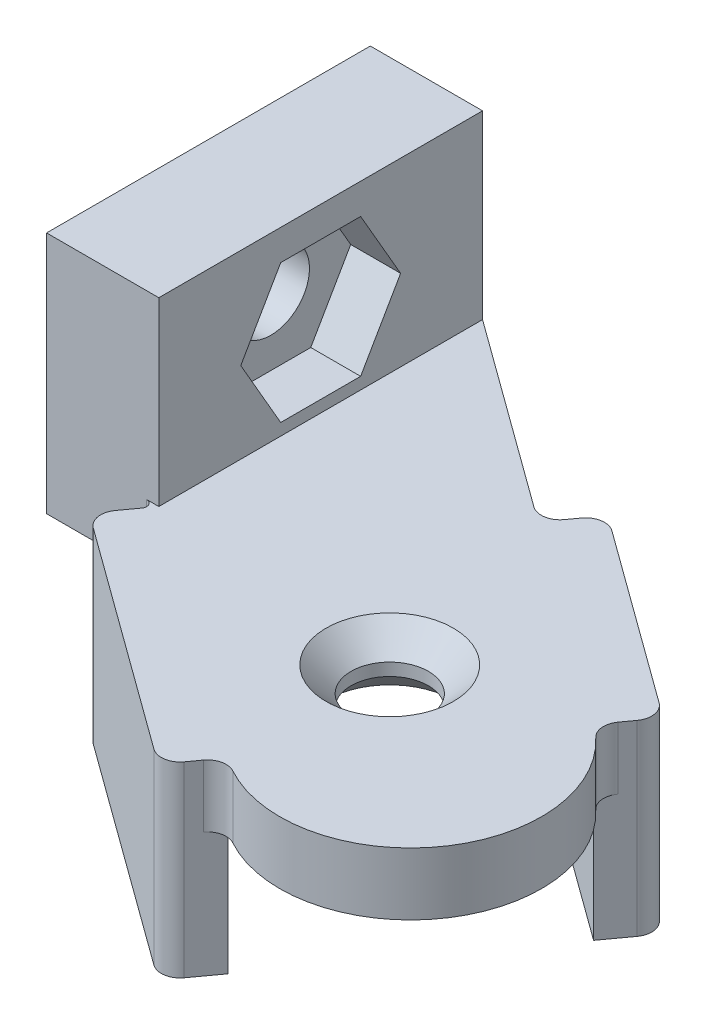
SolidWorks part; units mm, degrees
material "PA 类型 6"
ref_plane "前视基准面" through (0, 0, 0) normal (0, 0, 1) x (1, 0, 0)
ref_plane "上视基准面" through (0, 0, 0) normal (0, 1, 0) x (1, 0, 0)
ref_plane "右视基准面" through (0, 0, 0) normal (1, 0, 0) x (0, 0, -1)
sketch "草图1" plane through (0, 0, 0) normal (0, 1, 0) x (1, 0, 0)
  line L0 (0, 0) -> (0, 12.2017) construction
  line L1 (0, 0) -> (15.21, 0) construction
  line L2 (0, 0) -> (11.3188, 8.2236) construction
  line L5 (6.1542, 2.018) -> (-0.0175, -6.4766) construction
  line L7 (-10.1244, 13.8452) -> (6.1542, 2.018)
  line L8 (-10.1244, 0.8664) -> (-0.0175, -6.4766)
  line L9 (-10.1244, 13.8452) -> (-10.1244, 0.8664)
  line L10 (0, 0) -> (-11.3188, 8.2236) construction
  circle A0 centre (0, 0) radius 1.55
  arc A2 (6.1542, 2.018) -> (-0.0175, -6.4766) centre (3.0684, -2.2293) cw
  dimension "D1" = 3.1
  dimension "D5" = 5.25
  dimension "D2" = 36
  dimension "D6" = 10.1244
  dimension "D7" = 5.25
extrude "基座" add sketch "草图1" along normal blind 2.5
sketch "草图2" plane through (0, 0, 0) normal (0, 1, 0) x (1, 0, 0)
  line L3 (6.1542, 2.018) -> (-10.1244, 13.8452) construction
  line L5 (0, 0) -> (19.4408, 0) construction
  line L6 (6.1542, 2.018) -> (-10.1244, 13.8452) construction
  line L7 (0, 0) -> (0, 16.8119) construction
  line L14 (0, 0) -> (-14.65, 10.6439) construction
  line L15 (-11.3, -0.7516) -> (-10.1244, 0.8664)
  line L16 (-1.1931, -8.0947) -> (-11.3, -0.7516)
  line L17 (-0.0175, -6.4766) -> (-1.1931, -8.0947)
  line L18 (-10.1244, 0.8664) -> (-0.0175, -6.4766)
  line L19 (7.3298, 3.6361) -> (-0.8095, 9.5496)
  line L20 (6.1542, 2.018) -> (7.3298, 3.6361)
  line L21 (-1.9851, 7.9316) -> (6.1542, 2.018)
  line L22 (-0.8095, 9.5496) -> (-1.9851, 7.9316)
  point P6 (-1.9851, 7.9316)
  dimension "D1" = 36
  dimension "D2" = 2
extrude "机臂限位" add sketch "草图2" against normal blind 7.5 from surface at 2.5 contours L18 L15 L16 L17 | L19 L22 L21 L20 starting at face at (-2.4662, 2.5, -1.7918)
sketch "草图3" plane through (0, 0, 0) normal (0, 1, 0) x (1, 0, 0)
  line L0 (-14.6244, 13.8452) -> (-10.1244, 13.8452)
  line L1 (-10.1244, 13.8452) -> (-10.1244, 0.8664)
  line L2 (-10.1244, 0.8664) -> (-14.6244, 0.8664)
  line L3 (-14.6244, 0.8664) -> (-14.6244, 13.8452)
  dimension "D1" = 4.5
extrude "限位-1" add sketch "草图3" along normal blind 9.75
sketch "草图4" plane through (0, 0, 0) normal (0, 0, 1) x (1, 0, 0)
  line L7 (-14.6244, 9.75) -> (-14.6244, 0) construction
  line L10 (-14.6244, 6.5) -> (-14.6244, 9.75)
  line L11 (-17.6244, 6.5) -> (-14.6244, 6.5)
  line L12 (-17.6244, -2.25) -> (-17.6244, 6.5)
  line L13 (-21.1244, -2.25) -> (-17.6244, -2.25)
  line L14 (-21.1244, 9.75) -> (-21.1244, -2.25)
  line L15 (-14.6244, 9.75) -> (-21.1244, 9.75)
  line L16 (-10.1244, 9.75) -> (-14.6244, 9.75) construction
  dimension "D5" = 3
  dimension "D6" = 3.5
  dimension "D7" = 3.25
  dimension "D8" = 8.75
chamfer "倒角1" distance 1 angle 45 2 edges at (0, 2.5, 1.55) (0, 0, 1.55)
fillet "圆角5" radius 0.75 7 edges at (-0.8095, -1.25, -9.5496) (7.3298, -1.25, -3.6361) (-1.1931, -1.25, 8.0947) (-11.3, -1.25, 0.7516) (-1.9851, 1.25, -7.9316) (6.1542, 1.25, -2.018) (-0.0175, 1.25, 6.4766)
sketch "草图5" plane through (-10.1244, 0, 0) normal (1, 0, 0) x (0, 0, -1)
  line L0 (0.8664, 9.75) -> (13.8452, 9.75) construction
  line L1 (10.5601, 5.75) -> (8.9579, 8.525)
  line L2 (8.9579, 8.525) -> (5.7537, 8.525)
  line L3 (5.7537, 8.525) -> (4.1515, 5.75)
  line L4 (4.1515, 5.75) -> (5.7537, 2.975)
  line L5 (5.7537, 2.975) -> (8.9579, 2.975)
  line L6 (8.9579, 2.975) -> (10.5601, 5.75)
  line L7 (7.3558, 15.1256) -> (7.3558, -0.4001) construction
  circle A0 centre (7.3558, 5.75) radius 2.775 construction
  point P12 (7.3558, 9.75)
  dimension "D1" = 5.55
  dimension "D2" = 4
extrude "切除-拉伸1" cut sketch "草图5" against normal blind 2
sketch "草图7" plane through (-10.1244, 0, 0) normal (1, 0, 0) x (0, 0, -1)
  line L0 (8.9579, 8.525) -> (5.7537, 8.525) construction
  circle A0 centre (7.3558, 5.75) radius 1.55
  point P7 (7.3558, 8.525)
  dimension "D1" = 3.1
extrude "切除-拉伸2" cut sketch "草图7" against normal up to surface (4.5 mm away) up to face at (-14.6244, 4.875, -7.3558)
fillet "圆角6" radius 0.25 1 edges at (-10.1244, 1.25, -0.8664)
